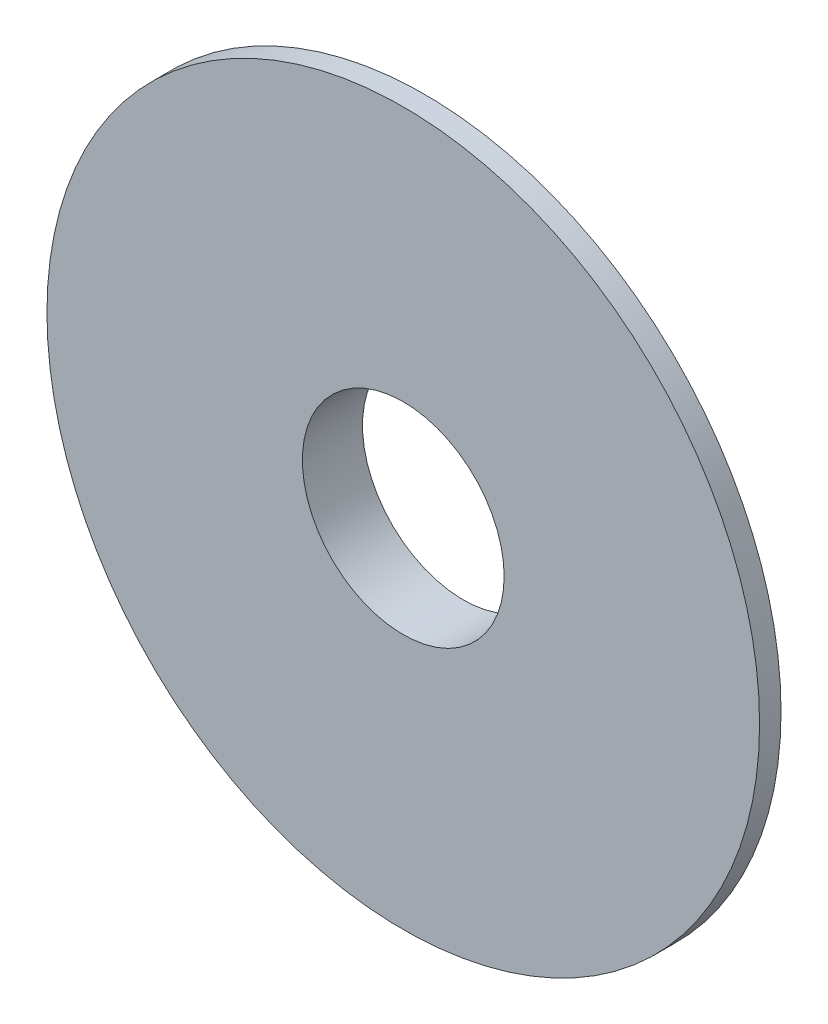
SolidWorks part; units mm, degrees
ref_plane "Спереди" through (0, 0, 0) normal (0, 0, 1) x (1, 0, 0)
ref_plane "Сверху" through (0, 0, 0) normal (0, 1, 0) x (1, 0, 0)
ref_plane "Справа" through (0, 0, 0) normal (1, 0, 0) x (0, 0, -1)
sketch "Эскиз1" plane through (0, 0, 0) normal (0, 0, 1) x (1, 0, 0)
  circle A0 centre (0, 0) radius 83
  circle A1 centre (0, 0) radius 23.5
extrude "Cover_web" add sketch "Эскиз1" along normal blind 5 from offset 35
sketch "Эскиз2" plane through (0, 0, 0) normal (0, 0, 1) x (1, 0, 0)
  circle A0 centre (0, 0) radius 27.5
  circle A1 centre (0, 0) radius 23.5
extrude "Bearing_boss" add sketch "Эскиз2" along normal blind 14 from offset 26
